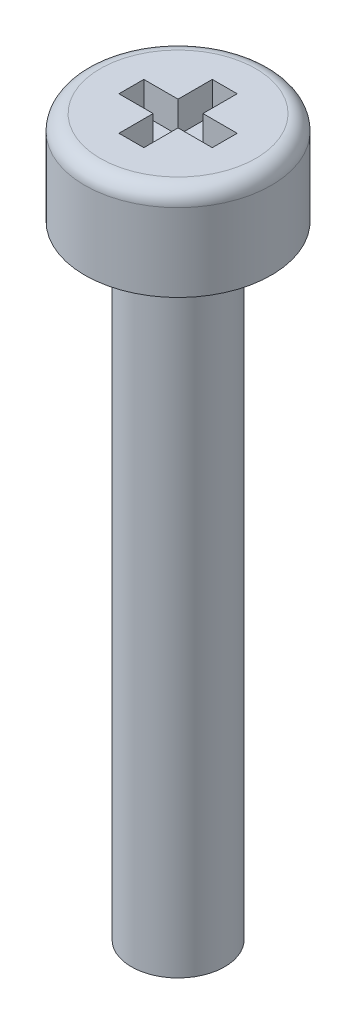
SolidWorks part; units mm, degrees
ref_plane "Front Plane" through (0, 0, 0) normal (0, 0, 1) x (1, 0, 0)
ref_plane "Top Plane" through (0, 0, 0) normal (0, 1, 0) x (1, 0, 0)
ref_plane "Right Plane" through (0, 0, 0) normal (1, 0, 0) x (0, 0, -1)
sketch "Sketch1" plane through (0, 0, 0) normal (0, 1, 0) x (1, 0, 0)
  circle A0 centre (0, 0) radius 3
  dimension "D1" = 6
extrude "Boss-Extrude1" add sketch "Sketch1" along normal blind 3
sketch "Sketch2" plane through (0, 0, 0) normal (0, -1, 0) x (1, 0, 0)
  circle A0 centre (0, 0) radius 1.5
  dimension "D1" = 3
extrude "Boss-Extrude2" add sketch "Sketch2" along normal blind 20
fillet "Fillet1" radius 0.5 1 edges at (0, 3, 3)
sketch "Sketch3" plane through (0, 3, 0) normal (0, 1, 0) x (1, 0, 0)
  line L1 (0.4, 1.5) -> (-0.4, 1.5)
  line L2 (0.4, 1.5) -> (0.4, -1.5)
  line L3 (0.4, -1.5) -> (-0.4, -1.5)
  line L4 (-0.4, 1.5) -> (-0.4, -1.5)
  line L5 (0.4, 1.5) -> (-0.4, -1.5) construction
  line L6 (0.4, -1.5) -> (-0.4, 1.5) construction
  line L7 (-1.5, 0.4) -> (1.5, 0.4)
  line L8 (-1.5, 0.4) -> (-1.5, -0.4)
  line L9 (-1.5, -0.4) -> (1.5, -0.4)
  line L10 (1.5, 0.4) -> (1.5, -0.4)
  line L11 (-1.5, 0.4) -> (1.5, -0.4) construction
  line L12 (-1.5, -0.4) -> (1.5, 0.4) construction
  point P0 (0, 0)
  point P6 (0, 0)
  dimension "D1" = 0.8
  dimension "D2" = 0.8
  dimension "D3" = 3
  dimension "D4" = 3
extrude "Cut-Extrude1" cut sketch "Sketch3" against normal blind 1 contours L4 L7 L2 L1 | L10 L7 L2 L9 | L9 L4 L3 L2 | L8 L9 L4 L7 | L4 L9 L2 L7
